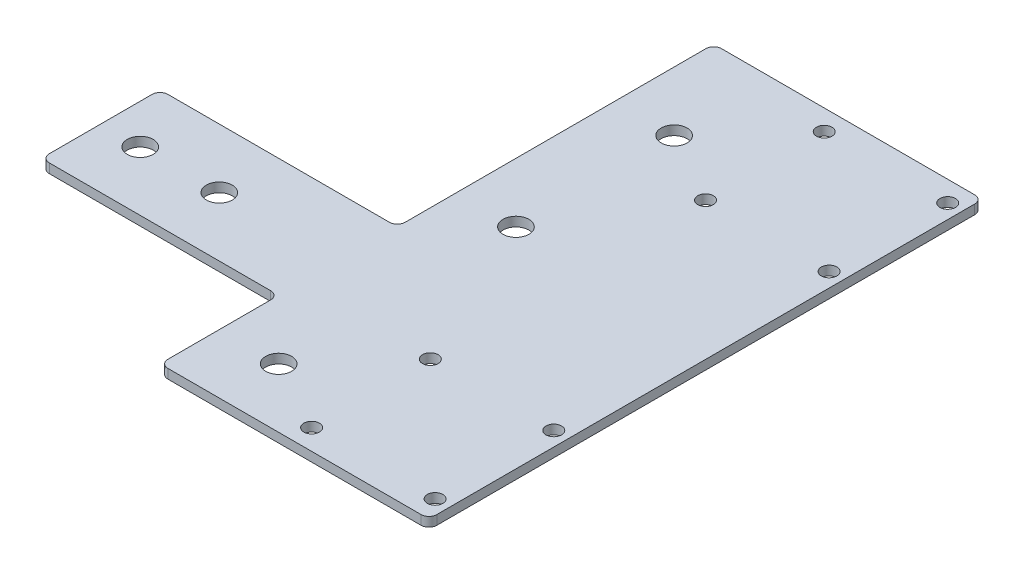
SolidWorks part; units mm, degrees
ref_plane "Front Plane" through (0, 0, 0) normal (0, 0, 1) x (1, 0, 0)
ref_plane "Top Plane" through (0, 0, 0) normal (0, 1, 0) x (1, 0, 0)
ref_plane "Right Plane" through (0, 0, 0) normal (1, 0, 0) x (0, 0, -1)
sketch "Sketch1" plane through (0, 0, 0) normal (0, 1, 0) x (1, 0, 0)
  line L0 (-108.6375, -53.5226) -> (-108.6375, -86.5426)
  line L1 (-106.0975, 88.7174) -> (-24.8175, 88.7174)
  line L2 (-106.0975, -89.0826) -> (-24.8175, -89.0826)
  line L3 (-22.2775, 86.1774) -> (-22.2775, -86.5426)
  line L4 (-108.6375, 86.1774) -> (-108.6375, -10.3426)
  line L5 (-111.1775, -50.9826) -> (-182.2975, -50.9826)
  line L6 (-111.1775, -12.8826) -> (-182.2975, -12.8826)
  line L7 (-184.8375, -48.4426) -> (-184.8375, -15.4226)
  circle A0 centre (-66.5475, 82.1174) radius 2.5
  circle A1 centre (-26.8975, 82.1174) radius 2.5
  circle A2 centre (-66.5475, 44.0174) radius 2.5
  circle A3 centre (-26.8975, 44.0174) radius 2.5
  circle A4 centre (-26.8975, -44.3826) radius 2.5
  circle A5 centre (-66.5475, -44.3826) radius 2.5
  circle A6 centre (-26.8975, -82.4826) radius 2.5
  circle A7 centre (-66.5475, -82.4826) radius 2.5
  circle A8 centre (-89.5875, -70.0326) radius 4.1656
  circle A11 centre (-89.5875, 6.1674) radius 4.1656
  arc A13 (-106.0975, -89.0826) -> (-108.6375, -86.5426) centre (-106.0975, -86.5426) cw
  arc A14 (-106.0975, 88.7174) -> (-108.6375, 86.1774) centre (-106.0975, 86.1774) ccw
  arc A15 (-182.2975, -12.8826) -> (-184.8375, -15.4226) centre (-182.2975, -15.4226) ccw
  arc A16 (-182.2975, -50.9826) -> (-184.8375, -48.4426) centre (-182.2975, -48.4426) cw
  circle A17 centre (-89.5875, 56.9674) radius 4.1656
  arc A19 (-108.6375, -53.5226) -> (-111.1775, -50.9826) centre (-111.1775, -53.5226) ccw
  arc A20 (-108.6375, -10.3426) -> (-111.1775, -12.8826) centre (-111.1775, -10.3426) cw
  circle A21 centre (-172.1375, -31.9326) radius 4.1656
  circle A22 centre (-146.7375, -31.9326) radius 4.1656
  arc A24 (-22.2775, -86.5426) -> (-24.8175, -89.0826) centre (-24.8175, -86.5426) cw
  arc A25 (-24.8175, 88.7174) -> (-22.2775, 86.1774) centre (-24.8175, 86.1774) cw
  circle A26 centre (-89.5875, -44.6326) radius 4.1656 [skipped]
  circle A27 centre (-89.5875, -19.2326) radius 4.1656 [skipped]
  circle A28 centre (-89.5875, 31.5674) radius 4.1656 [skipped]
  point P58 (-108.6375, -50.9826)
  dimension "D3" = 39.65
  dimension "D4" = 5
  dimension "D6" = 4.62
  dimension "D8" = 38.1
  dimension "D5" = 39.65
  dimension "D15" = 86.36
  dimension "D16" = 2.54
  dimension "D7" = 2.54
  dimension "D25" = 2.54
  dimension "D26" = 12.7
  dimension "D9" = 38.1
  dimension "D10" = 6.6
  dimension "D11" = 38.1
  dimension "D12" = 38.1
  dimension "D13" = 54.9885
  dimension "D18" = 6.6
  dimension "D19" = 44.7
  dimension "D20" = 6.6
  dimension "D21" = 177.8
  dimension "D22" = 38.1
  dimension "D23" = 38.1
  dimension "D24" = 76.2
  dimension "D28" = 4.62
  dimension "D29" = 39.65
  dimension "D30" = 4.62
  dimension "D31" = 86.36
  dimension "D27" = 2
extrude "Boss-Extrude1" add sketch "Sketch1" along normal blind 3
